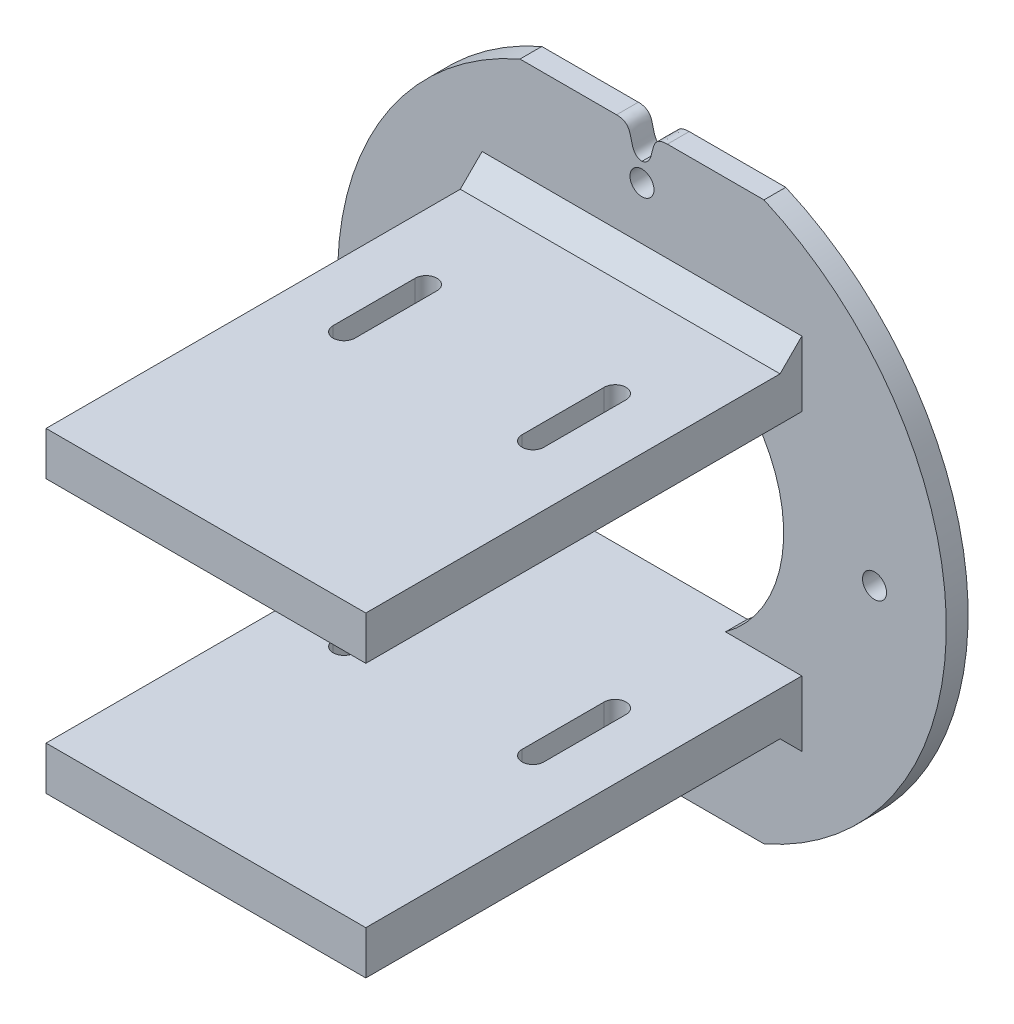
SolidWorks part; units mm, degrees
material "PE High Density"
ref_plane "Front Plane" through (0, 0, 0) normal (0, 0, 1) x (1, 0, 0)
ref_plane "Top Plane" through (0, 0, 0) normal (0, 1, 0) x (1, 0, 0)
ref_plane "Right Plane" through (0, 0, 0) normal (1, 0, 0) x (0, 0, -1)
sketch "Sketch1" plane through (0, 0, 0) normal (0, 0, 1) x (1, 0, 0)
  line L0 (-965.7469, 30.954) -> (-16.7854, 38.37) construction
  line L1 (-959.8471, -38.37) -> (-16.7854, -38.37) construction
  line L4 (-16.7854, -38.37) -> (-3.5, -38.37)
  line L5 (-16.7854, 38.37) -> (-3.5, 38.37)
  line L6 (0, 47.026) -> (0, 19.5) construction
  line L7 (3.5, 38.37) -> (16.7854, 38.37)
  line L8 (3.5, -38.37) -> (16.7854, -38.37)
  line L9 (-1000, -15.75) -> (49000, -15.75) construction
  line L10 (11.4973, -15.75) -> (-11.4973, -15.75)
  line L11 (11.4973, 15.75) -> (-11.4973, 15.75)
  line L13 (-1000, 0) -> (49000, 0) construction
  line L14 (16.7854, 38.37) -> (49040.1794, 38.3584) construction
  line L15 (0, 15.75) -> (0, -56.0206) construction
  line L24 (16.7854, 38.37) -> (49034.2746, 38.3584) construction
  line L27 (-19.5, 0) -> (19.5, 0) construction
  line L28 (42, 0) -> (49000, 0) construction
  arc A2 (11.4973, -15.75) -> (11.4973, 15.75) centre (0, 0) ccw
  arc A3 (16.7854, -38.37) -> (16.7854, 38.37) centre (0, 0) ccw
  arc A4 (-16.7854, 38.37) -> (-16.7854, -38.37) centre (0, 0) ccw
  arc A5 (-11.4973, 15.75) -> (-11.4973, -15.75) centre (0, 0) ccw
  spline S0 degree 3 poles (-3.5, 38.37) (-2.4877, 38.37) (-1.1809, 37.2525) (-1.493, 34.7416) (0, 34.57) knots 0 0 0 0 0.364574 1 1 1 1
  spline S1 degree 3 poles (3.5, 38.37) (2.5225, 38.37) (1.1173, 37.4414) (1.4621, 34.8622) (0, 34.57) knots 0 0 0 0 0.352043 1 1 1 1
  spline S2 degree 3 poles (3.5, -38.37) (2.5225, -38.37) (1.1173, -37.4414) (1.4621, -34.8622) (0, -34.57) knots 0 0 0 0 0.352043 1 1 1 1
  spline S3 degree 3 poles (-3.5, -38.37) (-2.4877, -38.37) (-1.1809, -37.2525) (-1.493, -34.7416) (0, -34.57) knots 0 0 0 0 0.364574 1 1 1 1
  dimension "D1" = 15.75
  dimension "D2" = 3.5
  dimension "D7" = 1
  dimension "D6" = 1
  dimension "D4" = 38.37
  dimension "D5" = 1.75
  dimension "D8" = 3.25
  dimension "D9" = 3.8
extrude "Boss-Extrude1" add sketch "Sketch1" along normal blind 3
sketch "Sketch3" plane through (0, 0, 0) normal (0, 0, -1) x (-1, 0, 0)
  line L1 (0, 47.7641) -> (0, -44.1879) construction
  circle A0 centre (0, 0) radius 32 construction
  point P5 (0, 32)
hole_wizard "Tap Drill for M4x0.7 Tap1" positions "3DSketch2" profile "Sketch4" hole size "M4x0.7" standard "ANSI Metric" end condition through all
sketch3d "3DSketch2"
  point P10 (0, 32, 0)
sketch "Sketch4" plane through (0, 32, 0) normal (1, 0, 0) x (0, 1, 0)
  line L0 (0, 0) -> (0, 3)
  line L1 (0, 3) -> (1.65, 3)
  line L2 (1.65, 3) -> (1.65, 0.025)
  line L3 (1.65, 0.025) -> (1.675, 0)
  line L5 (1.675, 0) -> (0, 0)
  line L6 (-1.65, 0.025) -> (-1.675, 0) construction
  line L11 (0, -6.35) -> (0, 107.95) construction
  dimension "Thru Hole Dia." = 3.3
  dimension "Thru Hole Depth" = 3
  dimension "Near C'Sink Dia." = 3.35
  dimension "Near C'Sink Angle" = 90
pattern_circular "CirPattern1" count 4 over 360 about axis through (0, 0, 0) along (0, 0, 1) of "Tap Drill for M4x0.7 Tap1"
sketch "Sketch6" plane through (0, 0, 3) normal (0, 0, 1) x (1, 0, 0)
  line L0 (28, -21.75) -> (28, 21.75) construction
  line L1 (-22, -15.75) -> (22, -15.75)
  line L2 (-22, -15.75) -> (-22, 15.75) construction
  line L3 (-22, 15.75) -> (22, 15.75)
  line L4 (22, -15.75) -> (22, 15.75) construction
  line L5 (-22, -15.75) -> (22, 15.75) construction
  line L6 (-22, 15.75) -> (22, -15.75) construction
  line L7 (-22, 21.75) -> (22, 21.75)
  line L8 (-28, -21.75) -> (-28, 21.75) construction
  line L9 (-22, -21.75) -> (22, -21.75)
  line L10 (-22, 15.75) -> (-22, 21.75)
  line L11 (-28, 21.75) -> (28, 21.75) construction
  line L12 (-22, -15.75) -> (-22, -21.75)
  line L13 (22, -15.75) -> (22, -21.75)
  line L14 (22, 21.75) -> (22, 15.75)
  line L15 (-28, -21.75) -> (28, -21.75) construction
  point P0 (0, 0)
  dimension "D1" = 31.5
  dimension "D2" = 44
  dimension "D3" = 6
sketch "Sketch10" [suppressed] plane through (0, 21.75, 0) normal (0, 1, 0) x (1, 0, 0)
  line L0 (0, -1063) -> (0, 48937) construction
  line L1 (22, -73) -> (-22, -73) construction
  line L2 (13, -1063) -> (13, 48937) construction
  line L3 (-13, -1063) -> (-13, 48937) construction
  line L6 (-14.5, -11.5) -> (-14.5, -37.5)
  line L8 (-11.5, -11.5) -> (-11.5, -37.5)
  line L9 (32, 0) -> (-32, 0) construction
  line L10 (11.5, -11.5) -> (11.5, -37.5)
  line L11 (14.5, -11.5) -> (14.5, -37.5)
  arc A0 (-11.5, -11.5) -> (-14.5, -11.5) centre (-13, -11.5) ccw
  arc A1 (-14.5, -37.5) -> (-11.5, -37.5) centre (-13, -37.5) ccw
  arc A2 (14.5, -37.5) -> (11.5, -37.5) centre (13, -37.5) cw
  arc A3 (11.5, -11.5) -> (14.5, -11.5) centre (13, -11.5) cw
  point P5 (0, -73)
  point P19 (-13, -10)
  point P24 (13, -10)
  dimension "D3" = 10
  dimension "D1" = 13
  dimension "D2" = 13
extrude "Cut-Extrude3" [suppressed] cut sketch "Sketch10" against normal blind 57
sketch "Sketch11" plane through (0, 0, 0) normal (1, 0, 0) x (0, 0, -1)
  line L0 (-1000, 0) -> (49000, 0) construction
  line L1 (-63, 21.747) -> (-63, 15.75)
  line L2 (-63, -993.0972) -> (-63, 49006.9028) construction
  line L3 (-63, -21.747) -> (48982.0861, -21.747) construction
  line L4 (-3, 38.37) -> (-3, -38.37) construction
  line L5 (-3, 38.37) -> (-3, -38.37) construction
  line L6 (-63, -15.75) -> (-63, -21.747)
  line L8 (-3, -15.75) -> (-3, -21.747)
  line L10 (-3, -21.747) -> (-63, -21.747)
  line L11 (-3, -15.75) -> (-63, -15.75)
  line L13 (-3, 21.747) -> (-63, 21.747)
  line L14 (-3, -15.75) -> (48994.615, -15.75) construction
  line L15 (-3, 15.75) -> (-63, 15.75)
  line L17 (-3, 15.75) -> (-3, 21.747)
  dimension "D2" = 31.5
  dimension "D1" = 60
  dimension "D3" = 5.997
  dimension "D4" = 5.997
sketch "Sketch9" plane through (28, 0, 0) normal (0, -1, 0) x (0, 0, -1)
  line L0 (-1087.4779, -28) -> (48912.5221, -28) construction
  line L2 (-10, -1060.4556) -> (-10, 48939.5444) construction
  line L3 (-32.5, -41) -> (48912.5221, -41) construction
  line L4 (0, -60) -> (0, 4) construction
  line L5 (-1087.4779, -15) -> (48912.5221, -15) construction
  line L6 (-19.7, -13.5) -> (-31, -13.5)
  line L7 (-19.7, -39.5) -> (-31, -39.5)
  line L9 (-19.7, -42.5) -> (-31, -42.5)
  line L10 (-19.7, -16.5) -> (-31, -16.5)
  line L11 (-1087.4779, -41) -> (48912.5221, -41) construction
  arc A0 (-19.7, -42.5) -> (-19.7, -39.5) centre (-19.7, -41) ccw
  arc A1 (-31, -39.5) -> (-31, -42.5) centre (-31, -41) ccw
  arc A2 (-31, -16.5) -> (-31, -13.5) centre (-31, -15) cw
  arc A3 (-19.7, -13.5) -> (-19.7, -16.5) centre (-19.7, -15) cw
  point P9 (-18.2, -41)
  point P29 (-32.5, -41)
  point P30 (-18.2, -41)
  dimension "D3" = 18.2
  dimension "D1" = 13
  dimension "D2" = 13
extrude "Boss-Extrude2" add sketch "Sketch11" along normal mid plane 44
extrude "Cut-Extrude4" cut sketch "Sketch9" against normal mid plane 70
sketch "Sketch12" plane through (0, 0, 0) normal (0, 0, -1) x (-1, 0, 0)
  circle A0 centre (0, 0) radius 19.5
chamfer "Chamfer1" distance 3 angle 45 1 edges at (0, 21.747, 3)
chamfer "Chamfer2" distance 3 angle 45 1 edges at (0, -21.747, 3)
